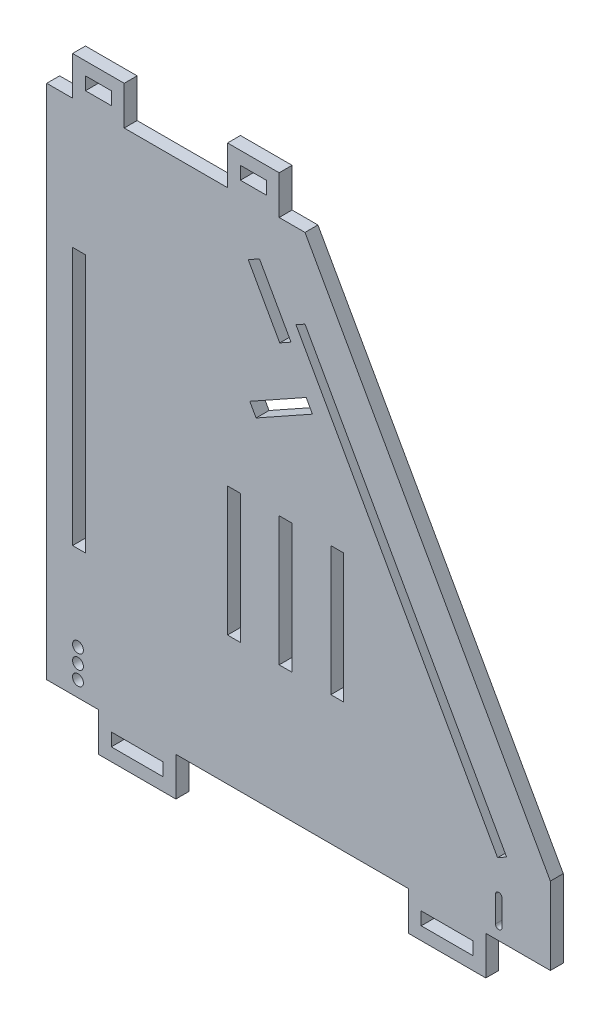
SolidWorks part; units mm, degrees
ref_plane "Front Plane" through (0, 0, 0) normal (0, 0, 1) x (1, 0, 0)
ref_plane "Top Plane" through (0, 0, 0) normal (0, 1, 0) x (1, 0, 0)
ref_plane "Right Plane" through (0, 0, 0) normal (1, 0, 0) x (0, 0, -1)
sketch "Sketch1" plane through (0, 0, 0) normal (0, 0, 1) x (1, 0, 0)
  line L0 (195, 30) -> (100, 200)
  line L1 (0, 0) -> (100, 0)
  line L2 (0, 0) -> (0, 200)
  line L3 (0, 200) -> (100, 200)
  line L4 (100, 0) -> (100, 200)
  line L5 (100, 0) -> (195, 0)
  line L6 (100, 0) -> (100, 30)
  line L7 (100, 30) -> (195, 30)
  line L8 (195, 0) -> (195, 30)
  dimension "D1" = 195
  dimension "D2" = 200
  dimension "D3" = 100
  dimension "D4" = 30
extrude "Boss-Extrude1" add sketch "Sketch1" along normal blind 5 contours L4 L7 L0 | L1 L4 L3 L2 | L5 L8 L7 L4
sketch "Sketch2" plane through (0, 0, 5) normal (0, 0, 1) x (1, 0, 0)
  line L0 (0, 0) -> (0, 200) construction
  line L1 (0, 0) -> (195, 0) construction
  circle A0 centre (12.1, 6) radius 2.1
  dimension "D1" = 4.2
  dimension "D2" = 12.1
  dimension "D3" = 6
extrude "Cut-Extrude1" cut sketch "Sketch2" against normal blind 5
sketch "Sketch3" plane through (0, 0, 5) normal (0, 0, 1) x (1, 0, 0)
  line L0 (0, 200) -> (100, 200) construction
  line L1 (10, 200) -> (30, 200)
  line L2 (10, 200) -> (10, 215)
  line L3 (10, 215) -> (30, 215)
  line L4 (30, 200) -> (30, 215)
  line L5 (0, 0) -> (0, 200) construction
  line L6 (50, 200) -> (50, 190.6568) construction
  line L7 (15, 210) -> (25, 210)
  line L8 (15, 210) -> (15, 205)
  line L9 (15, 205) -> (25, 205)
  line L10 (25, 210) -> (25, 205)
  line L11 (75, 210) -> (75, 205)
  line L12 (85, 205) -> (75, 205)
  line L13 (85, 210) -> (85, 205)
  line L14 (85, 210) -> (75, 210)
  line L15 (70, 200) -> (70, 215)
  line L16 (90, 215) -> (70, 215)
  line L17 (90, 200) -> (90, 215)
  line L18 (90, 200) -> (70, 200)
  dimension "D1" = 10
  dimension "D2" = 20
  dimension "D3" = 15
  dimension "D4" = 5
  dimension "D5" = 5
  dimension "D6" = 5
  dimension "D7" = 5
extrude "Boss-Extrude2" add sketch "Sketch3" against normal blind 5
sketch "Sketch4" plane through (0, 0, 5) normal (0, 0, 1) x (1, 0, 0)
  circle A0 centre (12.1, 6) radius 2.1 construction
  circle A1 centre (12.1, 6) radius 2.1
  circle A2 centre (12.1, 11.5) radius 2.1
  circle A3 centre (12.1, 17) radius 2.1
  dimension "D1" = 3
extrude "Cut-Extrude2" cut sketch "Sketch4" against normal blind 5 contours A2 | A3
sketch "Sketch5" plane through (0, 0, 5) normal (0, 0, 1) x (1, 0, 0)
  line L0 (0, 0) -> (195, 0) construction
  line L1 (20, 0) -> (50, 0)
  line L2 (20, 0) -> (20, -15)
  line L3 (20, -15) -> (50, -15)
  line L4 (50, 0) -> (50, -15)
  line L5 (0, 0) -> (0, 200) construction
  line L7 (25, -10) -> (45, -10)
  line L8 (25, -10) -> (25, -5)
  line L9 (25, -5) -> (45, -5)
  line L10 (45, -10) -> (45, -5)
  line L11 (145, -10) -> (145, -5)
  line L12 (165, -5) -> (145, -5)
  line L13 (165, -10) -> (165, -5)
  line L14 (165, -10) -> (145, -10)
  line L15 (140, 0) -> (140, -15)
  line L16 (170, -15) -> (140, -15)
  line L17 (170, 0) -> (170, -15)
  line L18 (170, 0) -> (140, 0)
  dimension "D1" = 15
  dimension "D2" = 20
  dimension "D3" = 30
  dimension "D4" = 5
  dimension "D5" = 5
  dimension "D6" = 5
  dimension "D7" = 5
  dimension "D8" = 90
  dimension "D9" = 5
  dimension "D10" = 30
  dimension "D11" = 5
extrude "Boss-Extrude3" add sketch "Sketch5" against normal blind 5
sketch "Sketch6" plane through (0, 0, 5) normal (0, 0, 1) x (1, 0, 0)
  line L0 (100, 169.251) -> (178.0514, 29.5801)
  line L1 (178.0514, 29.5801) -> (174.5596, 27.6288)
  line L2 (174.5596, 27.6288) -> (96.5082, 167.2998)
  line L3 (96.5082, 167.2998) -> (100, 169.251)
  line L4 (195, 30) -> (100, 200) construction
  dimension "D1" = 4
  dimension "D2" = 160
  dimension "D3" = 15
extrude "Cut-Extrude3" cut sketch "Sketch6" against normal blind 5
sketch "Sketch7" plane through (0, 0, 5) normal (0, 0, 1) x (1, 0, 0)
  line L0 (50, 0) -> (140, 0) construction
  line L1 (75, 100) -> (70, 100)
  line L2 (75, 100) -> (75, 50)
  line L3 (75, 50) -> (70, 50)
  line L4 (70, 100) -> (70, 50)
  line L5 (195, 0) -> (195, 30) construction
  line L6 (95, 100) -> (90, 100)
  line L7 (95, 100) -> (95, 50)
  line L8 (95, 50) -> (90, 50)
  line L9 (90, 100) -> (90, 50)
  line L10 (115, 100) -> (110, 100)
  line L11 (115, 100) -> (115, 50)
  line L12 (115, 50) -> (110, 50)
  line L13 (110, 100) -> (110, 50)
  point P6 (75, 75)
  dimension "D1" = 5
  dimension "D2" = 50
  dimension "D3" = 50
  dimension "D4" = 120
  dimension "D5" = 3
extrude "Cut-Extrude4" cut sketch "Sketch7" against normal blind 5
sketch "Sketch8" plane through (0, 0, 5) normal (0, 0, 1) x (1, 0, 0)
  line L0 (175, 15) -> (175, 5) construction
  line L1 (176.25, 15) -> (176.25, 5)
  line L2 (173.75, 15) -> (173.75, 5)
  line L3 (195, 0) -> (195, 30) construction
  line L4 (170, 0) -> (195, 0) construction
  arc A0 (176.25, 15) -> (173.75, 15) centre (175, 15) ccw
  arc A1 (173.75, 5) -> (176.25, 5) centre (175, 5) ccw
  point P2 (175, 10)
  dimension "D1" = 1.25
  dimension "D2" = 20
  dimension "D3" = 10
  dimension "D4" = 5
extrude "Cut-Extrude5" cut sketch "Sketch8" against normal blind 5
sketch "Sketch9" plane through (0, 0, 5) normal (0, 0, 1) x (1, 0, 0)
  line L0 (78.6257, 132.6773) -> (100.4493, 144.8728)
  line L1 (100.4493, 144.8728) -> (102.8884, 140.5081)
  line L2 (102.8884, 140.5081) -> (81.0648, 128.3126)
  line L3 (81.0648, 128.3126) -> (78.6257, 132.6773)
  line L4 (50, 0) -> (140, 0) construction
  line L5 (10, 150) -> (15, 150)
  line L6 (10, 150) -> (10, 50)
  line L7 (10, 50) -> (15, 50)
  line L8 (15, 150) -> (15, 50)
  line L9 (0, 0) -> (0, 200) construction
  line L11 (96.5082, 167.2998) -> (174.5596, 27.6288) construction
  line L12 (100, 169.251) -> (96.5082, 167.2998) construction
  point P8 (12.5, 50)
  dimension "D1" = 5
  dimension "D2" = 100
  dimension "D3" = 50
  dimension "D4" = 10
  dimension "D5" = 5
  dimension "D6" = 25
  dimension "D7" = 7.5
  dimension "D8" = 21.5
extrude "Cut-Extrude6" cut sketch "Sketch9" against normal blind 5
sketch "Sketch10" plane through (0, 0, 0) normal (0, 0, -1) x (-1, 0, 0)
  line L0 (-94.5826, 160.4959) -> (-82.3871, 182.3195)
  line L1 (-82.3871, 182.3195) -> (-78.0224, 179.8804)
  line L2 (-78.0224, 179.8804) -> (-90.2179, 158.0568)
  line L3 (-90.2179, 158.0568) -> (-94.5826, 160.4959)
  line L4 (-195, 30) -> (-100, 200) construction
  line L5 (-100, 169.251) -> (-96.5082, 167.2998) construction
  line L6 (-96.5082, 167.2998) -> (-174.5596, 27.6288) construction
  dimension "D1" = 25
  dimension "D2" = 5
  dimension "D3" = 5
  dimension "D4" = 5
extrude "Cut-Extrude7" cut sketch "Sketch10" against normal blind 5
